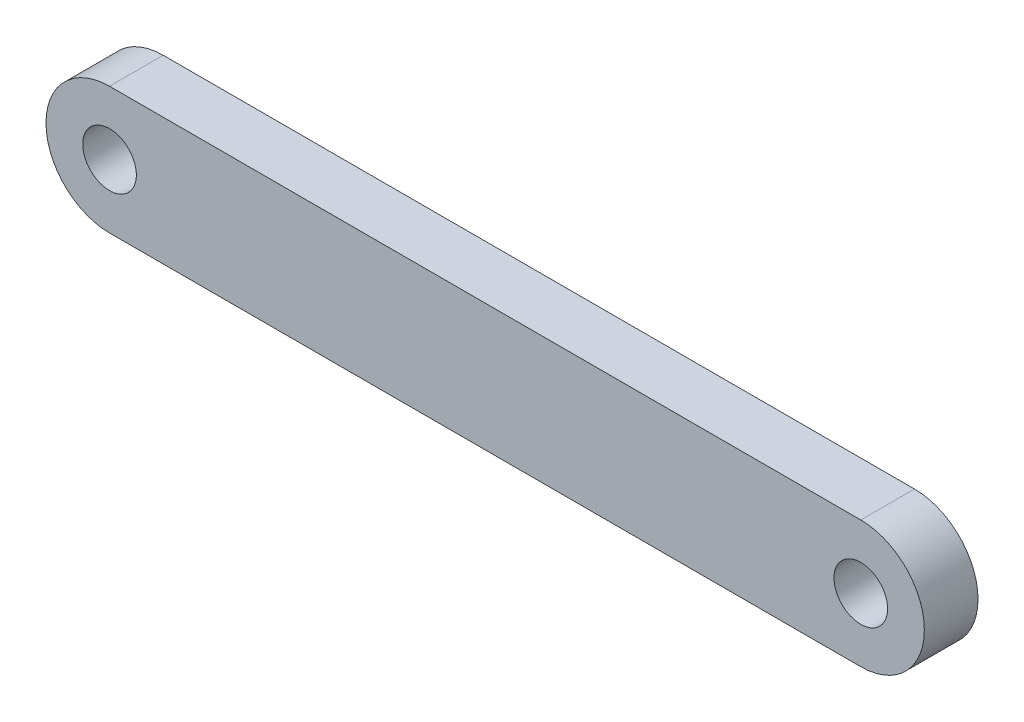
SolidWorks part; units mm, degrees
ref_plane "Front Plane" through (0, 0, 0) normal (0, 0, 1) x (1, 0, 0)
ref_plane "Top Plane" through (0, 0, 0) normal (0, 1, 0) x (1, 0, 0)
ref_plane "Right Plane" through (0, 0, 0) normal (1, 0, 0) x (0, 0, -1)
sketch "Sketch1" plane through (0, 0, 0) normal (0, 0, 1) x (1, 0, 0)
  line L0 (-13.8947, 0) -> (14.1053, 0) construction
  line L1 (-13.8947, 2.3684) -> (14.1053, 2.3684)
  line L2 (-13.8947, -2.3684) -> (14.1053, -2.3684)
  arc A0 (-13.8947, 2.3684) -> (-13.8947, -2.3684) centre (-13.8947, 0) ccw
  arc A1 (14.1053, -2.3684) -> (14.1053, 2.3684) centre (14.1053, 0) ccw
  circle A2 centre (14.1053, 0) radius 1
  circle A3 centre (-13.8947, 0) radius 1
  point P3 (0.1053, 0)
  dimension "D1" = 28
extrude "Boss-Extrude1" add sketch "Sketch1" along normal blind 2
